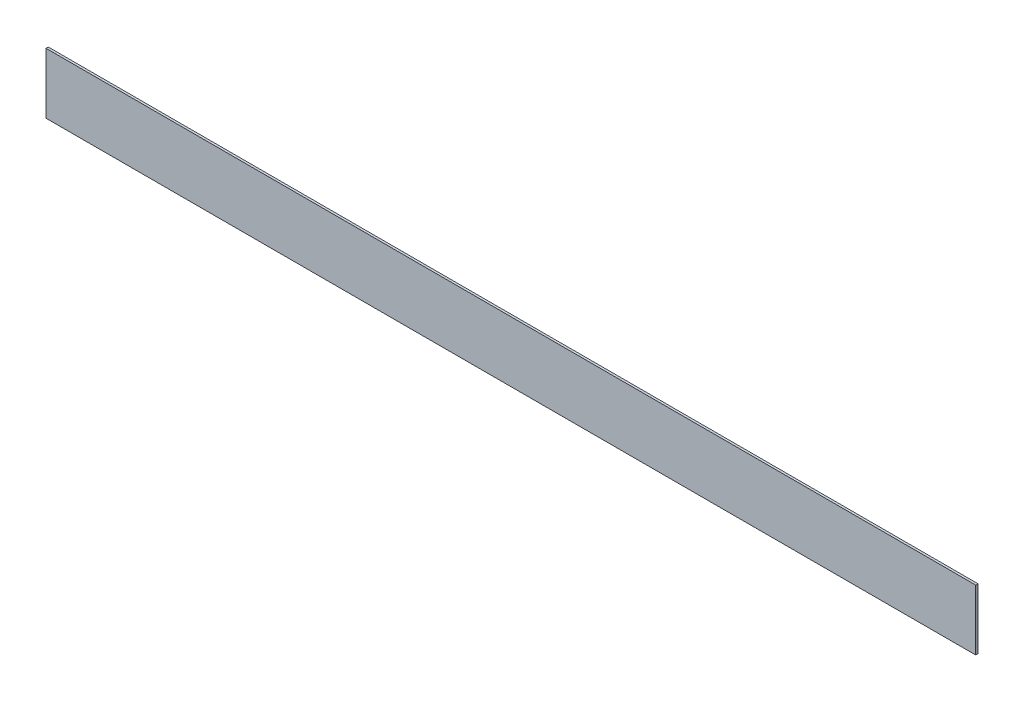
SolidWorks part; units mm, degrees
ref_plane "前视基准面" through (0, 0, 0) normal (0, 0, 1) x (1, 0, 0)
ref_plane "上视基准面" through (0, 0, 0) normal (0, 1, 0) x (1, 0, 0)
ref_plane "右视基准面" through (0, 0, 0) normal (1, 0, 0) x (0, 0, -1)
other "Configuration Table"
sketch "草图1" plane through (0, 0, 0) normal (0, 0, 1) x (1, 0, 0)
  line L1 (0, 0) -> (2056, 0)
  line L2 (0, 0) -> (0, -134)
  line L3 (0, -134) -> (2056, -134)
  line L4 (2056, 0) -> (2056, -134)
  dimension "D1" = 134
  dimension "D2" = 2056
extrude "凸台-拉伸1" add sketch "草图1" along normal blind 5
